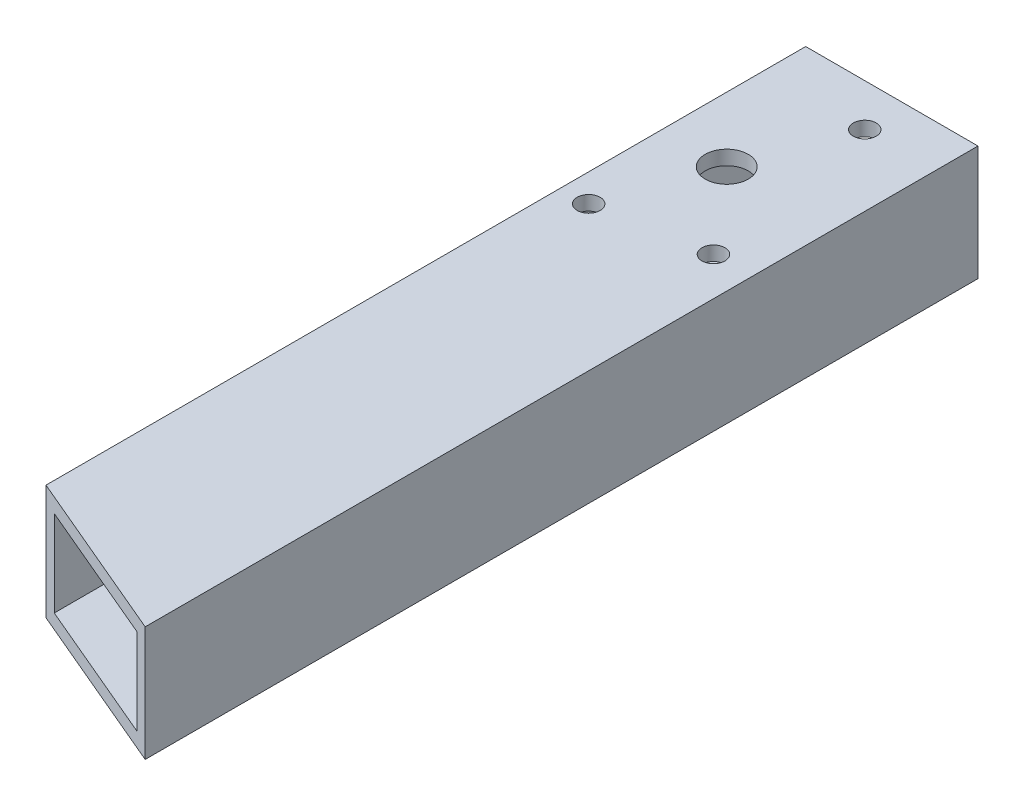
SolidWorks part; units mm, degrees
ref_plane "Front Plane" through (0, 0, 0) normal (0, 0, 1) x (1, 0, 0)
ref_plane "Top Plane" through (0, 0, 0) normal (0, 1, 0) x (1, 0, 0)
ref_plane "Right Plane" through (0, 0, 0) normal (1, 0, 0) x (0, 0, -1)
sketch "Sketch1" plane through (0, 0, 0) normal (0, 0, 1) x (1, 0, 0)
  line L1 (-19.05, 12.7) -> (19.05, 12.7)
  line L2 (-19.05, 12.7) -> (-19.05, -12.7)
  line L3 (-19.05, -12.7) -> (19.05, -12.7)
  line L4 (19.05, 12.7) -> (19.05, -12.7)
  line L5 (-19.05, 12.7) -> (19.05, -12.7) construction
  line L6 (-19.05, -12.7) -> (19.05, 12.7) construction
  line L7 (-15.875, 9.525) -> (15.875, 9.525)
  line L8 (-15.875, 9.525) -> (-15.875, -9.525)
  line L9 (-15.875, -9.525) -> (15.875, -9.525)
  line L10 (15.875, 9.525) -> (15.875, -9.525)
  line L11 (-15.875, 9.525) -> (15.875, -9.525) construction
  line L12 (-15.875, -9.525) -> (15.875, 9.525) construction
  point P0 (0, 0)
  point P6 (0, 0)
  dimension "D1" = 38.1
  dimension "D2" = 25.4
  dimension "D3" = 19.05
  dimension "D4" = 31.75
extrude "Boss-Extrude1" add sketch "Sketch1" along normal blind 184.15
sketch "Sketch2" plane through (0, 12.7, 0) normal (0, 1, 0) x (1, 0, 0)
  line L0 (19.05, -184.15) -> (-19.05, -167.9775)
  line L1 (-19.05, -184.15) -> (-19.05, 0) construction
  line L2 (-19.05, -167.9775) -> (-19.05, -184.15)
  line L3 (-19.05, -184.15) -> (19.05, -184.15)
  dimension "D1" = 23
extrude "Cut-Extrude1" cut sketch "Sketch2" against normal up to surface (25.4 mm away) up to face at (0, -12.7, 92.075)
sketch "Sketch3" plane through (0, 12.7, 0) normal (0, 1, 0) x (1, 0, 0)
  line L0 (-19.05, -167.9775) -> (-19.05, 0) construction
  line L1 (19.05, 0) -> (-19.05, 0) construction
  circle A0 centre (-4.7625, -31.75) radius 4.7625
  circle A2 centre (-12.9069, -54.1264) radius 2.54
  circle A5 centre (3.3819, -9.3736) radius 2.54
  circle A7 centre (10.5439, -49.9914) radius 2.54
  arc A8 (18.9953, -30.1364) -> (18.1144, -25.1407) centre (18.6882, -27.615) ccw [skipped]
  arc A9 (-18.0388, -11.982) -> (-21.9248, -15.2427) centre (-20.0689, -13.5086) ccw [skipped]
  arc A10 (-28.5203, -33.3636) -> (-27.6394, -38.3593) centre (-28.2132, -35.885) ccw [skipped]
  point P24 (-4.7625, -31.75)
  dimension "D2" = 31.75
  dimension "D3" = 9.525
  dimension "D6" = 5.08
  dimension "D1" = 14.2875
  dimension "D7" = 6
extrude "Cut-Extrude2" cut sketch "Sketch3" against normal up to surface (25.4 mm away) up to face at (0, -12.7, 88.0319)
